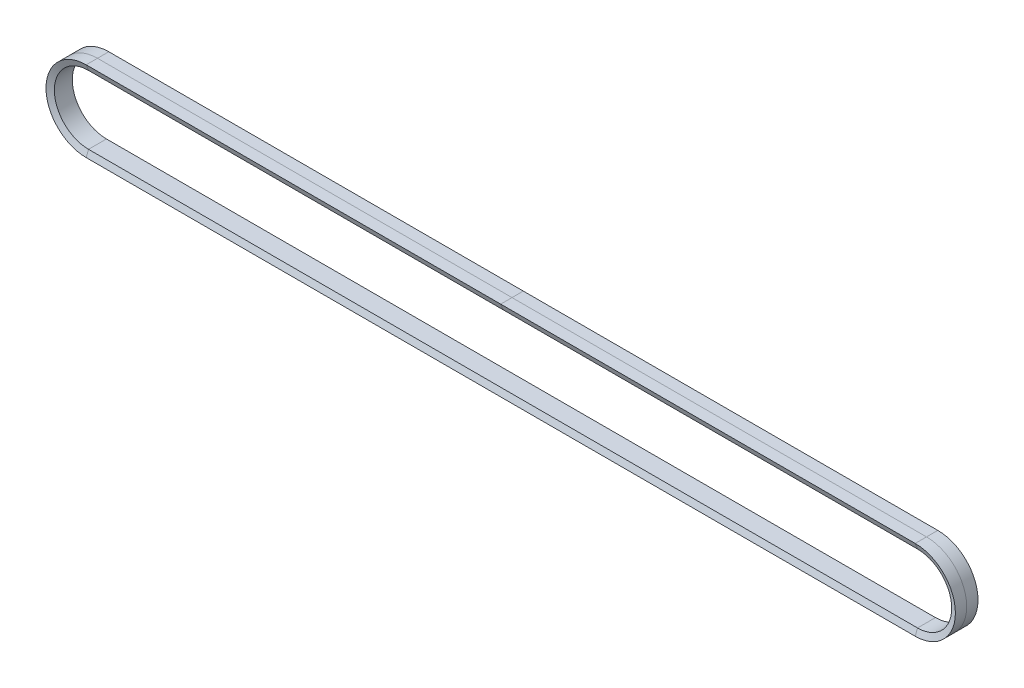
SolidWorks part; units mm, degrees
ref_plane "前视基准面" through (0, 0, 0) normal (0, 0, 1) x (1, 0, 0)
ref_plane "上视基准面" through (0, 0, 0) normal (0, 1, 0) x (1, 0, 0)
ref_plane "右视基准面" through (0, 0, 0) normal (1, 0, 0) x (0, 0, -1)
sketch "草图1" plane through (0, 0, 0) normal (0, 0, 1) x (1, 0, 0)
  line L0 (165, -16) -> (-165, -16)
  line L1 (165, 16) -> (-165, 16)
  arc A0 (165, -16) -> (165, 16) centre (165, 0) ccw
  arc A1 (-165, -16) -> (-165, 16) centre (-165, 0) cw
sketch "草图2" plane through (0, 0, 0) normal (1, 0, 0) x (0, 0, -1)
  line L0 (0, 16) -> (4.5, 16)
  line L1 (0, 16) -> (0, -16) construction
  line L2 (4.5, 16) -> (3.5705, 13.6)
  line L3 (3.5705, 13.6) -> (-3.5705, 13.6)
  line L4 (-3.5705, 13.6) -> (-4.5, 16)
  line L5 (-4.5, 16) -> (0, 16)
  dimension "D1" = 9
  dimension "D2" = 2.4
sweep "扫描1" add profiles "草图2" path "草图1"
